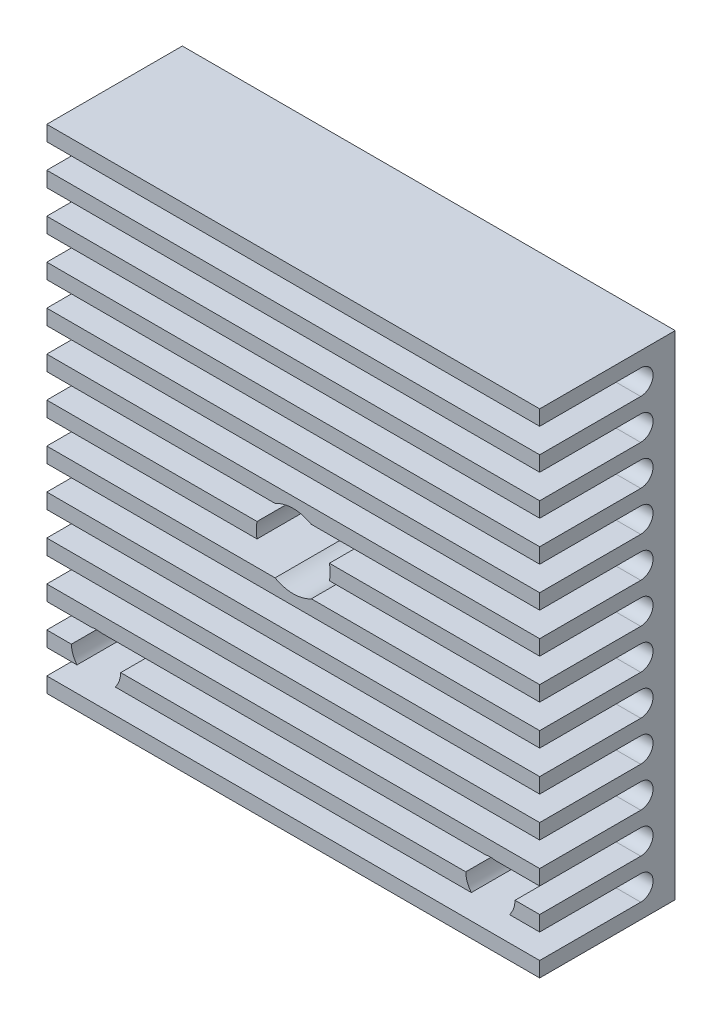
SolidWorks part; units mm, degrees
ref_plane "Ön Düzlem" through (0, 0, 0) normal (0, 0, 1) x (1, 0, 0)
ref_plane "Üst Düzlem" through (0, 0, 0) normal (0, 1, 0) x (1, 0, 0)
ref_plane "Sağ Düzlem" through (0, 0, 0) normal (1, 0, 0) x (0, 0, -1)
sketch "Sketch1" plane through (0, 0, 0) normal (0, 0, 1) x (1, 0, 0)
  line L1 (-20, -20) -> (20, -20)
  line L2 (-20, -20) -> (-20, 20)
  line L3 (-20, 20) -> (20, 20)
  line L4 (20, -20) -> (20, 20)
  line L5 (-20, -20) -> (20, 20) construction
  line L6 (-20, 20) -> (20, -20) construction
  point P0 (0, 0)
  dimension "D1" = 40
  dimension "D2" = 40
extrude "Boss-Extrude1" add sketch "Sketch1" along normal blind 11
sketch "Sketch3" plane through (20, 0, 0) normal (1, 0, 0) x (0, 0, -1)
  line L0 (-2.8, -17.769) -> (-2.8, -14.538) construction
  line L1 (-2.8, -14.538) -> (-2.8, -11.307) construction
  line L2 (-2.8, -11.307) -> (-2.8, -8.076) construction
  line L3 (-2.8, -8.076) -> (-2.8, -4.845) construction
  line L4 (-2.8, -4.845) -> (-2.8, -1.614) construction
  line L5 (-2.8, -1.614) -> (-2.8, 1.617) construction
  line L6 (-2.8, 1.617) -> (-2.8, 4.848) construction
  line L7 (-2.8, 4.848) -> (-2.8, 8.079) construction
  line L8 (-2.8, 8.079) -> (-2.8, 11.31) construction
  line L9 (-2.8, 11.31) -> (-2.8, 14.541) construction
  line L10 (-11, -20) -> (0, -20) construction
  line L13 (0, -20) -> (0, 20) construction
  line L14 (-2.8, 14.541) -> (-2.8, 17.772) construction
  line L15 (-11, -20) -> (-11, 20) construction
  line L16 (-11, -18.769) -> (-11, -16.769)
  line L17 (-2.8, -16.769) -> (-11, -16.769)
  line L18 (-2.8, -18.769) -> (-11, -18.769)
  line L19 (-2.8, -13.538) -> (-11, -13.538)
  line L20 (-2.8, -15.538) -> (-11, -15.538)
  line L21 (-2.8, -10.307) -> (-11, -10.307)
  line L22 (-2.8, -12.307) -> (-11, -12.307)
  line L23 (-2.8, -7.076) -> (-11, -7.076)
  line L24 (-2.8, -9.076) -> (-11, -9.076)
  line L25 (-2.8, -3.845) -> (-11, -3.845)
  line L26 (-2.8, -5.845) -> (-11, -5.845)
  line L27 (-2.8, -0.614) -> (-11, -0.614)
  line L28 (-2.8, -2.614) -> (-11, -2.614)
  line L29 (-2.8, 2.617) -> (-11, 2.617)
  line L30 (-2.8, 0.617) -> (-11, 0.617)
  line L31 (-2.8, 5.848) -> (-11, 5.848)
  line L32 (-2.8, 3.848) -> (-11, 3.848)
  line L33 (-2.8, 9.079) -> (-11, 9.079)
  line L34 (-2.8, 7.079) -> (-11, 7.079)
  line L35 (-2.8, 12.31) -> (-11, 12.31)
  line L36 (-2.8, 10.31) -> (-11, 10.31)
  line L37 (-2.8, 15.541) -> (-11, 15.541)
  line L38 (-2.8, 13.541) -> (-11, 13.541)
  line L39 (-2.8, 18.772) -> (-11, 18.772)
  line L40 (-2.8, 16.772) -> (-11, 16.772)
  line L41 (-11, -15.538) -> (-11, -13.538)
  line L42 (-11, -12.307) -> (-11, -10.307)
  line L43 (-11, -9.076) -> (-11, -7.076)
  line L44 (-11, -5.845) -> (-11, -3.845)
  line L45 (-11, -2.614) -> (-11, -0.614)
  line L46 (-11, 0.617) -> (-11, 2.617)
  line L47 (-11, 3.848) -> (-11, 5.848)
  line L48 (-11, 7.079) -> (-11, 9.079)
  line L49 (-11, 10.31) -> (-11, 12.31)
  line L50 (-11, 13.541) -> (-11, 15.541)
  line L51 (-11, 16.772) -> (-11, 18.772)
  arc A0 (-2.8, -15.538) -> (-2.8, -13.538) centre (-2.8, -14.538) ccw
  arc A1 (-2.8, -9.076) -> (-2.8, -7.076) centre (-2.8, -8.076) ccw
  arc A2 (-2.8, -2.614) -> (-2.8, -0.614) centre (-2.8, -1.614) ccw
  arc A3 (-2.8, 0.617) -> (-2.8, 2.617) centre (-2.8, 1.617) ccw
  arc A4 (-2.8, 3.848) -> (-2.8, 5.848) centre (-2.8, 4.848) ccw
  arc A5 (-2.8, 7.079) -> (-2.8, 9.079) centre (-2.8, 8.079) ccw
  arc A6 (-2.8, 10.31) -> (-2.8, 12.31) centre (-2.8, 11.31) ccw
  arc A7 (-2.8, 13.541) -> (-2.8, 15.541) centre (-2.8, 14.541) ccw
  arc A8 (-2.8, -5.845) -> (-2.8, -3.845) centre (-2.8, -4.845) ccw
  arc A9 (-2.8, -12.307) -> (-2.8, -10.307) centre (-2.8, -11.307) ccw
  arc A10 (-2.8, -18.769) -> (-2.8, -16.769) centre (-2.8, -17.769) ccw
  arc A11 (-2.8, 16.772) -> (-2.8, 18.772) centre (-2.8, 17.772) ccw
  dimension "D1" = 2
  dimension "D4" = 2.8
  dimension "D2" = 3.231
  dimension "D3" = 2.231
extrude "Cut-Extrude1" cut sketch "Sketch3" against normal through all
sketch "Sketch4" plane through (0, 0, 0) normal (0, 0, -1) x (-1, 0, 0)
  line L0 (16, -15.5) -> (-16, -15.5) construction
  line L1 (20, -20) -> (-20, -20) construction
  circle A0 centre (16, -15.5) radius 2
  circle A1 centre (-16, -15.5) radius 2
  circle A2 centre (0, 0) radius 3
  point P4 (0, -15.5)
  dimension "D2" = 4
  dimension "D3" = 4.5
  dimension "D4" = 6
  dimension "D1" = 32
extrude "Cut-Extrude2" cut sketch "Sketch4" against normal through all
